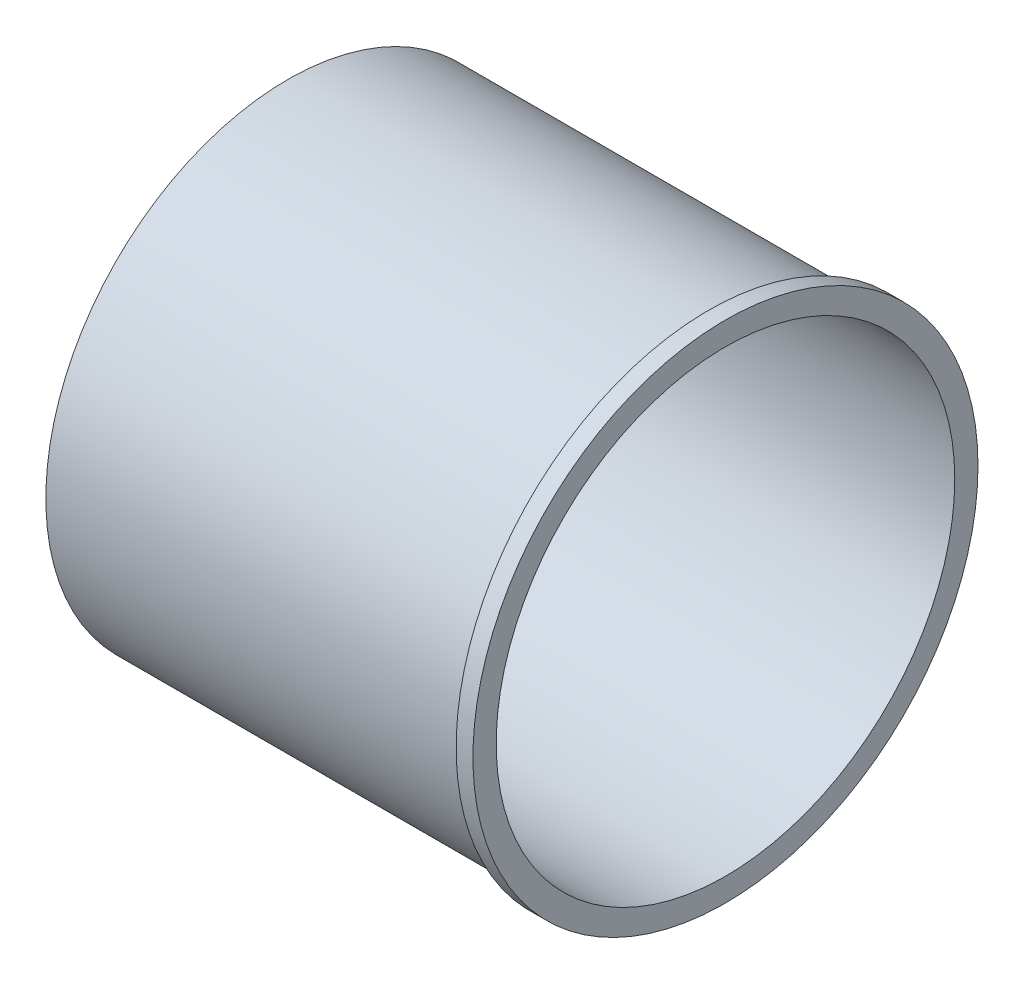
SolidWorks part; units mm, degrees
ref_plane "Front Plane" through (0, 0, 0) normal (1, 0, 0) x (0, 1, 0)
ref_plane "Top Plane" through (0, 0, 0) normal (0, 0, 1) x (0, 1, 0)
ref_plane "Right Plane" through (0, 0, 0) normal (0, 1, 0) x (-1, 0, 0)
sketch "Sketch1" plane through (0, 0, 0) normal (1, 0, 0) x (0, 1, 0)
  circle A0 centre (0, 0) radius 36.4998
  circle A1 centre (0, 0) radius 34.5948
  dimension "D1" = 72.9996
  dimension "D2" = 1.905
extrude "Boss-Extrude1" add sketch "Sketch1" along normal blind 63.5
sketch "Sketch2" plane through (63.5, 0, 0) normal (1, 0, 0) x (0, 1, 0)
  circle A0 centre (0, 0) radius 34.5948 construction
  circle A1 centre (0, 0) radius 34.5948
  circle A2 centre (0, 0) radius 38.1
  dimension "D1" = 76.2
extrude "Boss-Extrude2" add sketch "Sketch2" along normal blind 2.54
